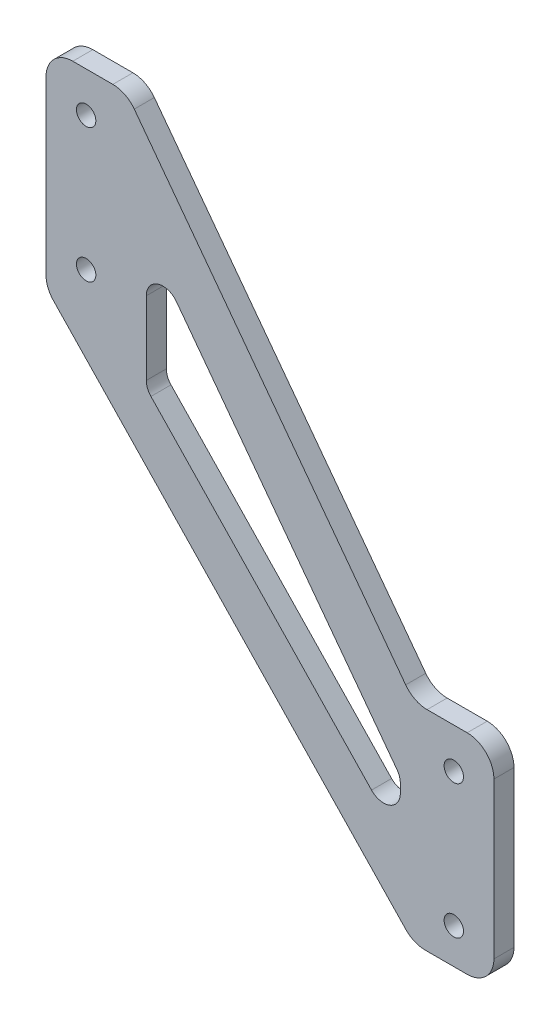
SolidWorks part; units mm, degrees
material "Thornel Mat VMA"
ref_plane "前视基准面" through (0, 0, 0) normal (0, 0, 1) x (1, 0, 0)
ref_plane "上视基准面" through (0, 0, 0) normal (0, 1, 0) x (1, 0, 0)
ref_plane "右视基准面" through (0, 0, 0) normal (1, 0, 0) x (0, 0, -1)
sketch "草图1" plane through (0, 0, 0) normal (0, 0, 1) x (1, 0, 0)
  line L0 (0, 0) -> (0, -20) construction
  line L1 (0, -20) -> (-55, 37.5) construction
  line L2 (-55, 37.5) -> (-55, 57.5) construction
  line L3 (-49, 63.5) -> (-61, 63.5)
  line L4 (-61, 63.5) -> (-61, 32.199)
  line L5 (-61, 32.199) -> (-6, -25.301)
  line L6 (-6, -25.301) -> (6, -25.301)
  line L7 (6, -25.301) -> (6, 6)
  line L9 (6, 6) -> (-6, 6)
  line L10 (-6, 6) -> (-49, 63.5)
  circle A0 centre (0, 0) radius 1.45
  circle A1 centre (0, -20) radius 1.45
  circle A2 centre (-55, 37.5) radius 1.45
  circle A3 centre (-55, 57.5) radius 1.45
  dimension "D1" = 2.9
  dimension "D2" = 20
  dimension "D3" = 20
  dimension "D4" = 55
  dimension "D5" = 37.5
  dimension "D6" = 6
  dimension "D7" = 6
  dimension "D8" = 12
  dimension "D9" = 8
  dimension "D10" = 6
  dimension "D11" = 12
  dimension "D12" = 12
  dimension "D13" = 6
extrude "凸台-拉伸1" add sketch "草图1" along normal blind 3
sketch "草图2" plane through (0, 0, 3) normal (0, 0, 1) x (1, 0, 0)
  line L0 (-46, 46.1302) -> (-46, 26.6442)
  line L2 (-8, -4.6837) -> (-46, 46.1302)
  line L3 (-6, 6) -> (-49, 63.5) construction
  line L4 (-46, 26.6442) -> (-8, -13.0831)
  line L5 (-8, -13.0831) -> (-8, -4.6837)
  line L6 (6, -25.301) -> (6, 6) construction
  line L7 (-61, 32.199) -> (-6, -25.301) construction
  line L8 (-61, 63.5) -> (-61, 32.199) construction
  dimension "D1" = 14
  dimension "D2" = 7
  dimension "D3" = 8
  dimension "D4" = 15
extrude "切除-拉伸1" cut sketch "草图2" against normal blind 3
fillet "圆角1" radius 4 7 edges at (-6, 6, 1.5) (6, 6, 1.5) (6, -25.301, 1.5) (-6, -25.301, 1.5) (-61, 32.199, 1.5) (-61, 63.5, 1.5) (-49, 63.5, 1.5)
fillet "圆角2" radius 2.5 4 edges at (-8, -13.0831, 1.5) (-46, 46.1302, 1.5) (-8, -4.6837, 1.5) (-46, 26.6442, 1.5)
